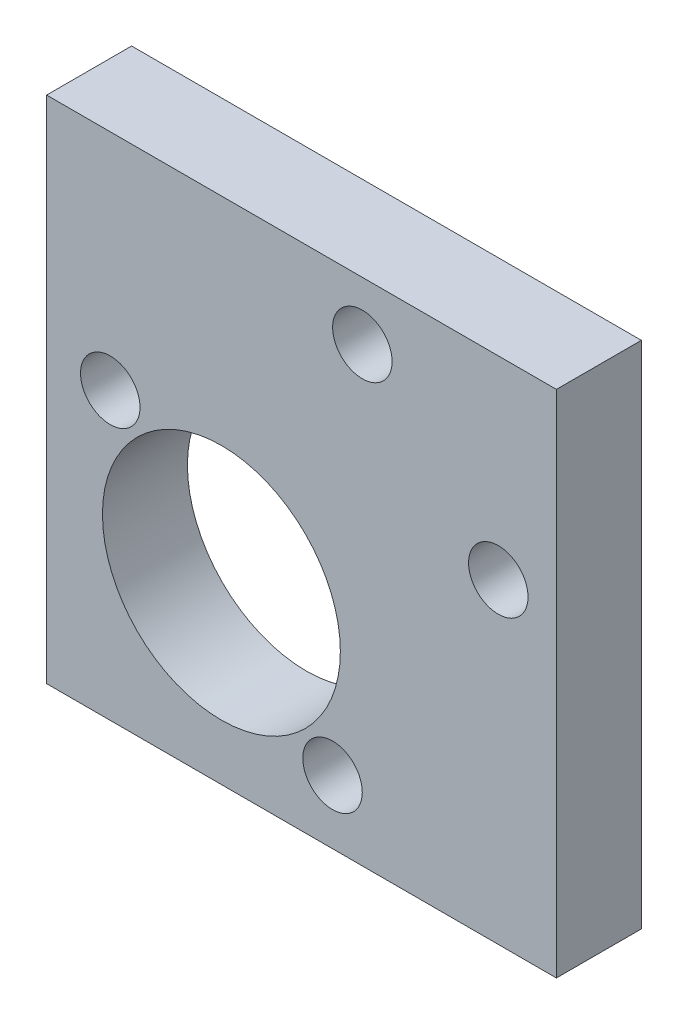
SolidWorks part; units mm, degrees
ref_plane "Piano frontale" through (0, 0, 0) normal (0, 0, 1) x (1, 0, 0)
ref_plane "Piano superiore" through (0, 0, 0) normal (0, 1, 0) x (1, 0, 0)
ref_plane "Piano destro" through (0, 0, 0) normal (1, 0, 0) x (0, 0, -1)
sketch "Schizzo1" plane through (0, 0, 0) normal (0, 0, 1) x (1, 0, 0)
  line L0 (30, 30) -> (0, 30)
  line L1 (0, 0) -> (36.6262, 36.6262) construction
  line L2 (30, 30) -> (30, 0)
  line L3 (0, 30) -> (0, 0)
  line L4 (0, 0) -> (30, 0)
  line L5 (10.285, 10.285) -> (1.0724, 19.4976) construction
  circle A0 centre (3.7443, 16.8257) radius 1.75
  circle A1 centre (16.8257, 3.7443) radius 1.75
  circle A4 centre (18.58, 26.58) radius 1.75
  circle A5 centre (26.58, 18.58) radius 1.75
  circle A8 centre (10.285, 10.285) radius 7
  dimension "D1" = 14
  dimension "D2" = 30
  dimension "D3" = 3.5
  dimension "D7" = 3.5
  dimension "D4" = 19.715
  dimension "D5" = 3.42
  dimension "D6" = 11.42
  dimension "D8" = 18.5
extrude "Estrusione-Estrusione1" add sketch "Schizzo1" along normal blind 5
